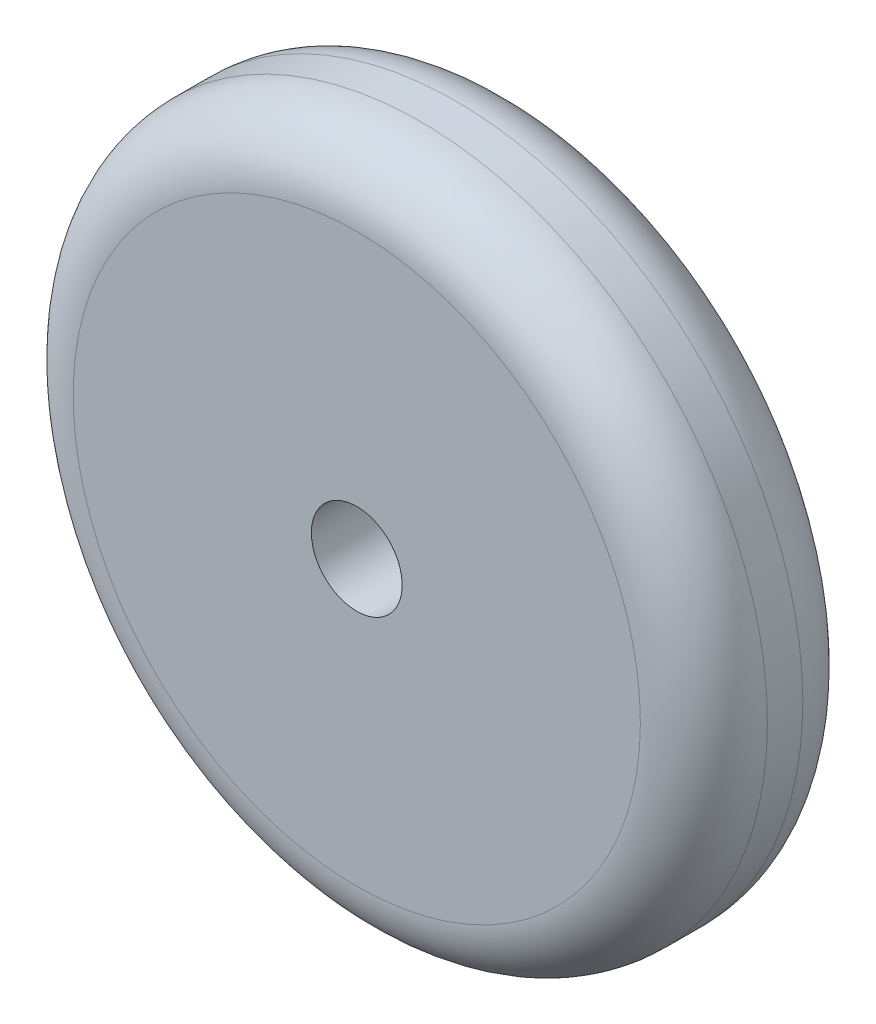
SolidWorks part; units mm, degrees
material "Rubber"
ref_plane "Front Plane" through (0, 0, 0) normal (0, 0, 1) x (1, 0, 0)
ref_plane "Top Plane" through (0, 0, 0) normal (0, 1, 0) x (1, 0, 0)
ref_plane "Right Plane" through (0, 0, 0) normal (1, 0, 0) x (0, 0, -1)
ref_plane "Plane1" through (0, 0, 0) normal (0, -1, 0) x (1, 0, 0)
sketch "Sketch1" plane through (0, 0, 0) normal (0, -1, 0) x (1, 0, 0)
  line L0 (12.7, 22.733) -> (12.7, -22.733)
  line L1 (12.7, -22.733) -> (97.155, -22.733)
  line L2 (97.155, -22.733) -> (97.155, 22.733)
  line L3 (97.155, 22.733) -> (12.7, 22.733)
  line L4 (0, 22.733) -> (0, -22.733) construction
revolve "Revolve1" add sketch "Sketch1" angle 360 about L4
fillet "Fillet1" radius 17.78 2 edges at (-97.155, 0, -22.733) (-97.155, 0, 22.733)
